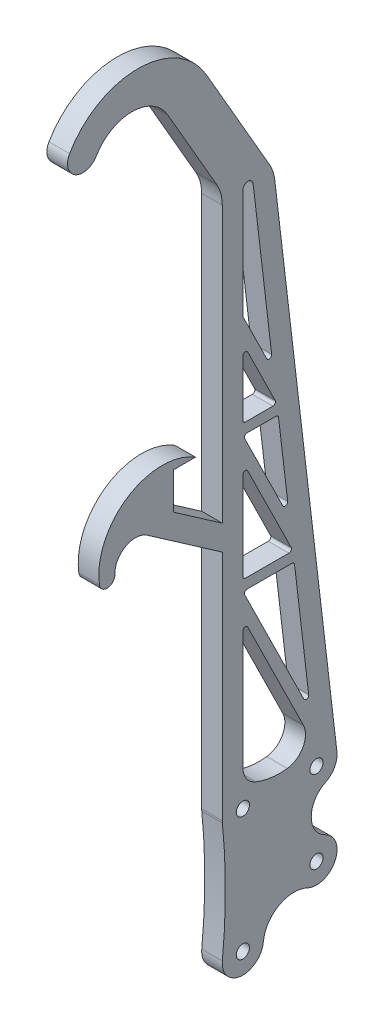
SolidWorks part; units mm, degrees
ref_plane "Front Plane" through (0, 0, 0) normal (0, 0, 1) x (1, 0, 0)
ref_plane "Top Plane" through (0, 0, 0) normal (0, 1, 0) x (1, 0, 0)
ref_plane "Right Plane" through (0, 0, 0) normal (1, 0, 0) x (0, 0, -1)
sketch "Sketch1" plane through (0, 0, 0) normal (1, 0, 0) x (0, 0, -1)
  line L1 (11.35, 19.05) -> (11.35, -6.35) construction
  line L2 (-11.35, -19.05) -> (-11.35, 19.05) construction
  line L3 (11.35, 0) -> (-11.35, 0) construction
  line L4 (-6.35, 19.05) -> (6.35, 19.05) construction
  line L5 (-17.7, 19.05) -> (-17.7, 183.3563)
  line L6 (8.5879, -12.0678) -> (-3.6653, -6.1486) construction
  line L7 (17.6561, 19.7951) -> (-1.825, 184.6629)
  line L8 (-11.35, 25.4) -> (-11.35, 69.85)
  line L9 (-56.5215, 215.9) -> (-71.6445, 189.7062) construction
  line L10 (-60.6459, 170.6563) -> (-30.4, 170.6563) construction
  line L11 (-19.4015, 189.7062) -> (-34.5244, 215.9)
  line L12 (-45.523, 209.55) -> (-60.6459, 183.3562) construction
  line L13 (-60.6459, 183.3562) -> (-30.4, 183.3562) construction
  line L14 (-30.4, 183.3562) -> (-45.523, 209.55) construction
  line L15 (-22.6094, 220.6625) -> (-1.825, 184.6629)
  line L16 (-1.825, 184.6629) -> (-12.8235, 178.3129) construction
  line L17 (-56.5215, 215.9) -> (-64.7704, 220.6625) construction
  line L18 (14.1121, -0.6322) -> (6.2486, 3.1664) construction
  line L19 (-11.35, 69.85) -> (10.6049, 25.3561)
  line L20 (10.6049, 25.3561) -> (-0.8043, 121.9108) construction
  line L21 (8.5879, 24.7678) -> (0.6662, 20.9411) construction
  line L22 (14.1121, 13.3322) -> (6.5563, 9.6822) construction
  line L23 (9.4901, 34.7905) -> (-11.35, 77.0252)
  line L24 (-11.35, 77.0252) -> (4.4995, 77.0252)
  line L25 (4.4995, 77.0252) -> (9.4901, 34.7905)
  line L26 (4.1244, 80.2002) -> (-11.35, 80.2002)
  line L27 (-11.35, 80.2002) -> (-11.35, 111.5606)
  line L28 (-11.35, 111.5606) -> (4.1244, 80.2002)
  line L29 (3.0096, 89.6346) -> (-11.35, 118.7358)
  line L30 (-11.35, 118.7358) -> (-0.4291, 118.7358)
  line L31 (-0.4291, 118.7358) -> (3.0096, 89.6346)
  line L32 (-0.8043, 121.9108) -> (-11.35, 121.9108)
  line L33 (-11.35, 121.9108) -> (-11.35, 143.2829)
  line L34 (-8.186, 184.3819) -> (-1.919, 131.3452)
  line L35 (-11.35, 69.85) -> (-8.5028, 71.2549) construction
  line L36 (-11.35, 77.0252) -> (-11.35, 80.2002) construction
  line L37 (-11.35, 111.5606) -> (-8.5028, 112.9656) construction
  line L38 (-11.35, 118.7358) -> (-11.35, 121.9108) construction
  line L39 (-0.8043, 121.9108) -> (-11.35, 143.2829)
  line L40 (-1.919, 131.3452) -> (-11.35, 150.4581)
  line L41 (-11.35, 143.2829) -> (-8.5028, 144.6878) construction
  line L42 (-1.919, 131.3452) -> (-1.3257, 126.3235) construction
  line L43 (-11.35, 150.4581) -> (-11.35, 184.1956)
  line L44 (-17.6679, -18.4122) -> (-15.1883, 6.15) construction
  line L45 (-5.0321, -19.6878) -> (-3.6653, -6.1486) construction
  circle A0 centre (-11.35, 19.05) radius 5 construction
  circle A1 centre (11.35, 19.05) radius 5 construction
  arc A2 (-17.6679, -18.4122) -> (-5.0321, -19.6878) centre (-11.35, -19.05) ccw
  arc A3 (8.5879, -12.0678) -> (14.1121, -0.6322) centre (11.35, -6.35) ccw
  arc A4 (14.1121, 13.3322) -> (17.6561, 19.7951) centre (11.35, 19.05) ccw
  arc A5 (14.1121, 13.3322) -> (14.1121, -0.6322) centre (17.485, 6.35) ccw
  arc A7 (-34.5244, 215.9) -> (-56.5215, 215.9) centre (-45.523, 209.55) ccw
  arc A8 (-71.6445, 189.7062) -> (-60.6459, 170.6563) centre (-60.6459, 183.3562) ccw construction
  arc A9 (-30.4, 170.6563) -> (-19.4015, 189.7062) centre (-30.4, 183.3562) ccw construction
  circle A10 centre (-45.523, 192.0875) radius 8.7312 construction
  arc A11 (-17.7, 183.3563) -> (-19.4015, 189.7062) centre (-30.4, 183.3563) ccw
  arc A12 (-56.5215, 215.9) -> (-64.7704, 220.6625) centre (-60.6459, 218.2813) cw
  arc A13 (-64.7704, 220.6625) -> (-22.6094, 220.6625) centre (-43.6899, 208.4917) cw
  arc A14 (-5.0321, -19.6878) -> (8.5879, -12.0678) centre (4.4447, -20.6445) cw
  arc A15 (-11.35, 25.4) -> (-8.5879, 24.7678) centre (-11.35, 19.05) cw
  arc A17 (10.6049, 25.3561) -> (8.5879, 24.7678) centre (11.35, 19.05) ccw
  arc A18 (8.5879, 24.7678) -> (-8.5879, 24.7678) centre (0, 42.5454) cw
  arc A19 (-11.35, 184.1956) -> (-8.186, 184.3819) centre (-9.7625, 184.1956) cw
  arc A20 (-17.7, 19.05) -> (-17.6679, 18.4122) centre (-11.35, 19.05) ccw
  arc A21 (-17.6679, -18.4122) -> (-17.6679, 18.4122) centre (-200.0545, 0) ccw
  point P11 (0, 0)
  point P47 (-11.35, 0)
  point P48 (-45.523, 222.25)
  dimension "D3" = 12.7
  dimension "D4" = 10
  dimension "D5" = 6.35
  dimension "D6" = 15.875
  dimension "D7" = 12.7
  dimension "D9" = 12.7
  dimension "D10" = 4.7625
  dimension "D12" = 6.35
  dimension "D14" = 3.175
  dimension "D15" = 1.5875
  dimension "D17" = 9.525
  dimension "D1" = 25.4
  dimension "D2" = 38.1
  dimension "D8" = 38.8937
  dimension "D11" = 222.25
  dimension "D13" = 6.35
  dimension "D16" = 44.45
extrude "Boss-Extrude1" add sketch "Sketch1" along normal mid plane 6.35
sketch "Sketch2" plane through (3.175, 0, 0) normal (1, 0, 0) x (0, 0, -1)
  line L0 (-11.35, -19.05) -> (-11.35, 19.05) construction
  circle A0 centre (11.35, -6.35) radius 2.032
  circle A1 centre (11.35, 19.05) radius 2.032
  circle A2 centre (-11.35, 19.05) radius 2.032
  circle A3 centre (-11.35, -19.05) radius 2.032
  dimension "D1" = 4.064
extrude "Cut-Extrude1" cut sketch "Sketch2" against normal through all
fillet "Fillet1" radius 12.7 1 edges at (0, 184.6629, 1.825)
fillet "Fillet2" radius 0.7937 15 edges at (0, 121.9108, 11.35) (0, 118.7358, 11.35) (0, 118.7358, 0.4291) (0, 89.6346, -3.0096) (0, 111.5606, 11.35) (0, 80.2002, 11.35) (0, 80.2002, -4.1244) (0, 69.85, 11.35) (0, 77.0252, 11.35) (0, 77.0252, -4.4995) (0, 34.7905, -9.4901) (0, 150.4581, 11.35) (0, 121.9108, 0.8043) (0, 143.2829, 11.35) (0, 131.3452, 1.919)
fillet "Fillet3" radius 6.35 2 edges at (0, 25.4, 11.35) (0, 25.3561, -10.6049)
sketch "Sketch3" plane through (3.175, 0, 0) normal (1, 0, 0) x (0, 0, -1)
  line L1 (-17.7, 183.3563) -> (-17.7, 19.05) construction
  line L2 (-17.7, 113.6632) -> (-17.7, 90.742)
  line L3 (-40.8261, 106.8144) -> (-17.7, 90.742)
  line L4 (-17.7, 113.6632) -> (-23.8691, 118.7218)
  arc A0 (-40.8261, 106.8144) -> (-50.7947, 101.3405) centre (-44.45, 101.6) ccw
  arc A1 (-23.8691, 118.7218) -> (-55.5701, 100.9076) centre (-36.2442, 103.63) ccw
  arc A2 (-55.5701, 100.9076) -> (-50.7947, 101.3405) centre (-53.1932, 101.2425) ccw
  point P3 (-17.7, 115.2333)
  point P11 (-36.2442, 103.63)
  point P12 (0, 0)
  dimension "D1" = 6.35
  dimension "D2" = 101.6
  dimension "D3" = 44.45
extrude "Boss-Extrude2" add sketch "Sketch3" against normal up to surface (6.35 mm away) up to face at (-3.175, -19.05, 9.318)
sketch "Sketch4" plane through (3.175, 0, 0) normal (1, 0, 0) x (0, 0, -1)
  line L0 (-17.7, 98.475) -> (-32.7224, 108.9154)
  line L1 (-32.7224, 108.9154) -> (-32.7224, 120.2194)
  line L2 (-32.7224, 120.2194) -> (-17.7, 120.2194)
  line L3 (-17.7, 120.2194) -> (-17.7, 98.475)
  line L4 (-40.8261, 106.8144) -> (-17.7, 90.742) construction
  line L5 (-17.7, 90.742) -> (-17.7, 19.05) construction
  dimension "D1" = 6.35
extrude "Cut-Extrude2" cut sketch "Sketch4" against normal through all
